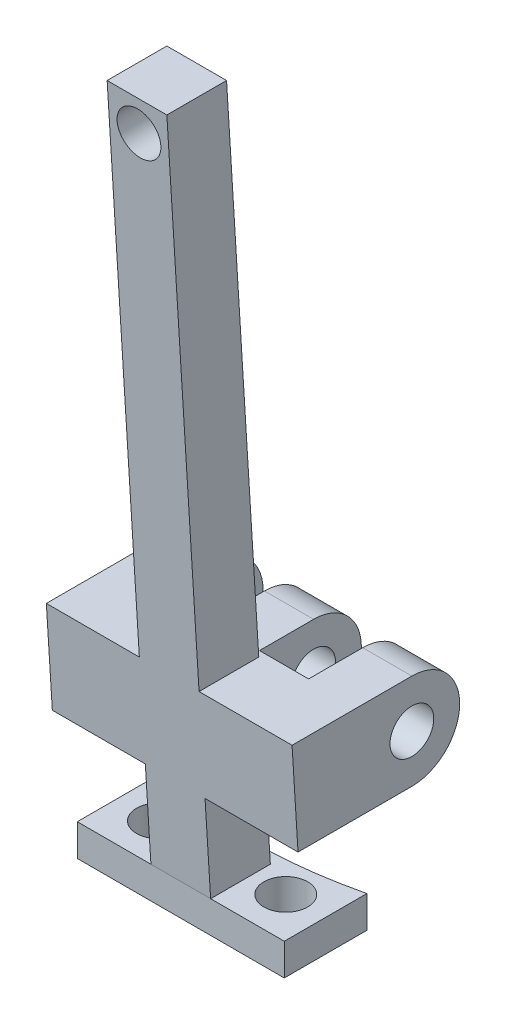
SolidWorks part; units mm, degrees
ref_plane "Front Plane" through (0, 0, 0) normal (0, 0, 1) x (1, 0, 0)
ref_plane "Top Plane" through (0, 0, 0) normal (0, 1, 0) x (1, 0, 0)
ref_plane "Right Plane" through (0, 0, 0) normal (1, 0, 0) x (0, 0, -1)
sketch "Sketch1" plane through (0, 0, 0) normal (0, 1, 0) x (1, 0, 0)
  line L0 (-6.5, 0) -> (6.5, 0)
  line L1 (-6.5, 0) -> (-6.5, 5.19)
  line L2 (6.5, 0) -> (6.5, 5.19)
  spline S0 degree 2 poles (-6.5, 5.19) (0, 3.63) (6.5, 5.19) knots 0 0 0 1 1 1
  point P4 (0, 0)
  dimension "D1" = 13
  dimension "D2" = 5.19
  dimension "D3" = 4.41
extrude "Boss-Extrude1" add sketch "Sketch1" along normal blind 2
sketch "Sketch2" plane through (0, 2, 0) normal (0, 1, 0) x (1, 0, 0)
  line L0 (-6.5, 2.595) -> (6.5, 2.595) construction
  line L1 (-6.5, 5.19) -> (-6.5, 0) construction
  line L2 (6.5, 0) -> (6.5, 5.19) construction
  circle A0 centre (-4, 2.595) radius 1.375
  circle A1 centre (4, 2.595) radius 1.375
  dimension "D3" = 2.75
  dimension "D1" = 2.5
  dimension "D2" = 2.5
extrude "Cut-Extrude1" cut sketch "Sketch2" against normal blind 2
sketch "Sketch4" plane through (0, 2, 0) normal (0, 1, 0) x (1, 0, 0)
  line L0 (-1.875, 3.75) -> (1.875, 3.75)
  line L1 (-1.875, 3.75) -> (-1.875, 0)
  line L2 (-6.5, 0) -> (6.5, 0) construction
  line L3 (-1.875, 0) -> (1.875, 0)
  line L4 (1.875, 0) -> (1.875, 3.75)
  point P2 (0, 3.75)
  dimension "D1" = 3.75
  dimension "D2" = 3.75
ref_plane "Plane1" through (0, 46, 0) normal (0, 1, 0) x (1, 0, 0)
sketch "Sketch6" plane through (0, 46, 0) normal (0, 1, 0) x (1, 0, 0)
  line L5 (-1.875, 1) -> (1.875, 1)
  line L6 (-1.875, 0) -> (1.875, 0) construction
  line L7 (-1.875, 1) -> (-1.875, -2.75)
  line L8 (-1.875, -2.75) -> (1.875, -2.75)
  line L9 (1.875, -2.75) -> (1.875, 1)
  line L10 (-1.875, 3.75) -> (-1.875, 0) construction
  line L11 (-1.875, 3.75) -> (1.875, 3.75) construction
  point P13 (0, 1)
  point P16 (0, 3.75)
  dimension "D1" = 1
loft "Loft2" add profiles "Sketch4", "Sketch6"
sketch "Sketch12" plane through (0, 0, 0) normal (0, 0, 1) x (1, 0, 0)
  line L0 (0, -1.1) -> (0, 1.1) construction
  line L1 (2.8603, 46) -> (-2.8603, 46) construction
  circle A0 centre (0, 44) radius 1.375
  dimension "D1" = 2.75
  dimension "D2" = 2
extrude "Cut-Extrude3" cut sketch "Sketch12" against normal through all both and the other way through all
sketch "Sketch8" plane through (0, 46, 0) normal (0, 1, 0) x (1, 0, 0)
  line L0 (-1.875, 1) -> (1.875, 1)
  line L1 (1.875, 1) -> (1.875, -9.75)
  line L2 (1.875, -9.75) -> (-1.875, -9.75)
  line L3 (-1.875, -9.75) -> (-1.875, 1)
  line L4 (-1.875, -2.75) -> (1.875, -2.75) construction
  dimension "D1" = 7
sketch "Sketch13" plane through (-1.875, 0, 0) normal (-1, 0, 0) x (0, 0, 1)
  line L0 (-3.3981, 13.63) -> (-3.3981, 7.63)
  line L1 (-3.75, 2) -> (-1, 46) construction
  line L2 (-3.3981, 7.63) -> (0.3519, 7.63)
  line L3 (0, 2) -> (2.75, 46) construction
  line L4 (0.3519, 7.63) -> (0.7269, 13.63)
  line L5 (0.7269, 13.63) -> (-3.3981, 13.63)
  point P9 (-3.6863, 13.63)
  dimension "D1" = 11.63
  dimension "D2" = 6
extrude "Boss-Extrude2" add sketch "Sketch13" along normal blind 5.84 and the other way up to surface (1.875 mm away) other way up to plane "Right Plane"
mirror "Mirror1" about plane through (0, 0, 0) normal (1, 0, 0) of "Boss-Extrude2"
sketch "Sketch16" plane through (-7.715, 0, 0) normal (-1, 0, 0) x (0, 0, 1)
  line L0 (-3.3981, 7.63) -> (-6.7981, 7.63)
  line L1 (-6.7981, 13.63) -> (-3.3981, 13.63)
  line L2 (-3.3981, 7.63) -> (-3.3981, 13.63)
  arc A0 (-6.7981, 13.63) -> (-6.7981, 7.63) centre (-6.7981, 10.63) ccw
  circle A1 centre (-6.7981, 10.63) radius 1.375
  dimension "D1" = 2.75
  dimension "D2" = 6
  dimension "D3" = 3.4
extrude "Boss-Extrude3" add sketch "Sketch16" against normal blind 3.086
pattern_linear "LPattern1" count 3 spacing 6.172 along (1, 0, 0) of "Boss-Extrude3"
